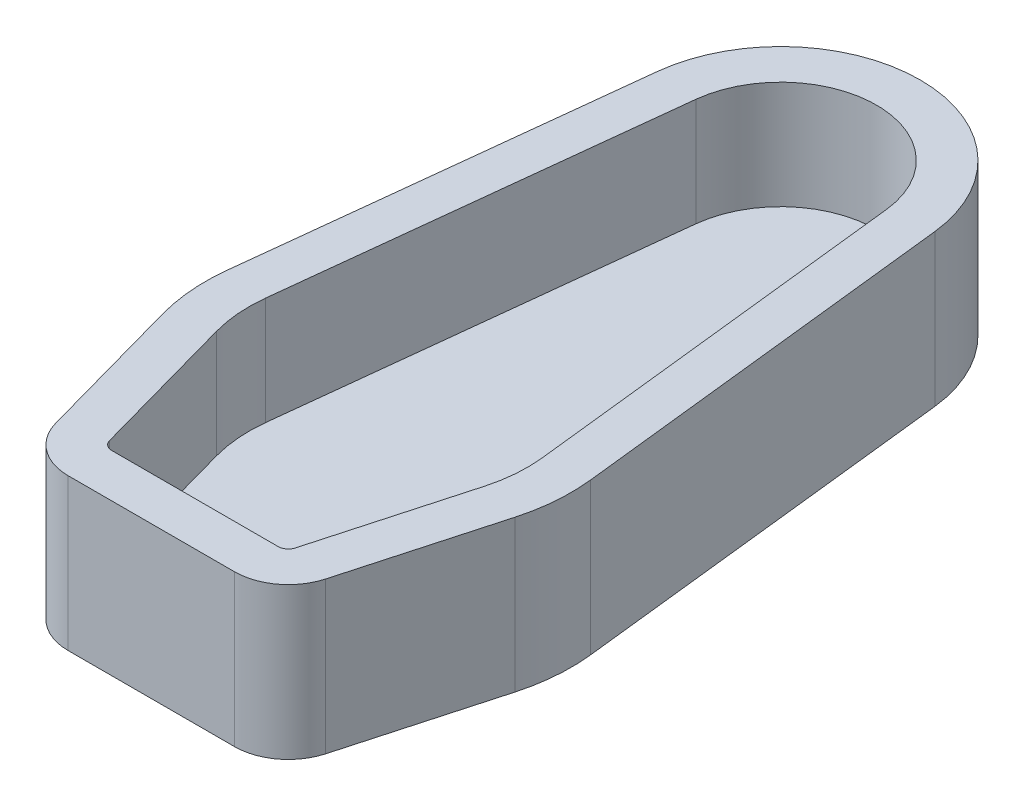
SolidWorks part; units mm, degrees
ref_plane "Front Plane" through (0, 0, 0) normal (0, 0, 1) x (1, 0, 0)
ref_plane "Top Plane" through (0, 0, 0) normal (0, 1, 0) x (1, 0, 0)
ref_plane "Right Plane" through (0, 0, 0) normal (1, 0, 0) x (0, 0, -1)
sketch "Sketch1" plane through (0, 0, 0) normal (0, 1, 0) x (1, 0, 0)
  line L0 (6.8678, 15.2626) -> (8.9976, -3.9181)
  line L1 (6.6829, -14.7119) -> (8.7194, -7.3806)
  line L2 (-4.12, -16.66) -> (4.12, -16.66)
  line L3 (-4.12, -14.5) -> (4.12, -14.5)
  line L4 (-4.6017, -14.1338) -> (-6.6382, -6.8025)
  line L5 (-4.721, 15.0242) -> (-6.8508, -4.1564)
  line L6 (4.721, 15.0242) -> (6.8508, -4.1564)
  line L7 (4.6017, -14.1338) -> (6.6382, -6.8025)
  line L8 (-6.6829, -14.7119) -> (-8.7194, -7.3806)
  line L9 (-6.8678, 15.2626) -> (-8.9976, -3.9181)
  arc A0 (4.721, 15.0242) -> (-4.721, 15.0242) centre (0, 14.5) ccw
  circle A1 centre (0, -5.5) radius 1.6
  arc A2 (4.12, -14.5) -> (4.6017, -14.1338) centre (4.12, -14) ccw
  arc A3 (-4.12, -14.5) -> (-4.6017, -14.1338) centre (-4.12, -14) cw
  arc A4 (6.6382, -6.8025) -> (6.8508, -4.1564) centre (-0.1064, -4.929) ccw
  arc A5 (-6.8508, -4.1564) -> (-6.6382, -6.8025) centre (0.1064, -4.929) ccw
  arc A6 (8.7194, -7.3806) -> (8.9976, -3.9181) centre (-0.1064, -4.929) ccw
  arc A7 (4.12, -16.66) -> (6.6829, -14.7119) centre (4.12, -14) ccw
  arc A8 (-4.12, -16.66) -> (-6.6829, -14.7119) centre (-4.12, -14) cw
  arc A9 (-8.9976, -3.9181) -> (-8.7194, -7.3806) centre (0.1064, -4.929) ccw
  arc A10 (6.8678, 15.2626) -> (-6.8678, 15.2626) centre (0, 14.5) ccw
  point P4 (0, 0)
  point P6 (0, 0)
  point P11 (0, -14.5)
  point P13 (0, -5.5)
  dimension "D2" = 9.5
  dimension "D1" = 3.2
  dimension "D3" = 0.5
  dimension "D4" = 0.5
  dimension "D5" = 7
  dimension "D6" = 2.16
extrude "Boss-Extrude3" add sketch "Sketch1" along normal blind 7.5 contours L0 A6 L1 A7 L2 A8 L8 A9 L9 A10
shell "Shell1" thickness 2.16
